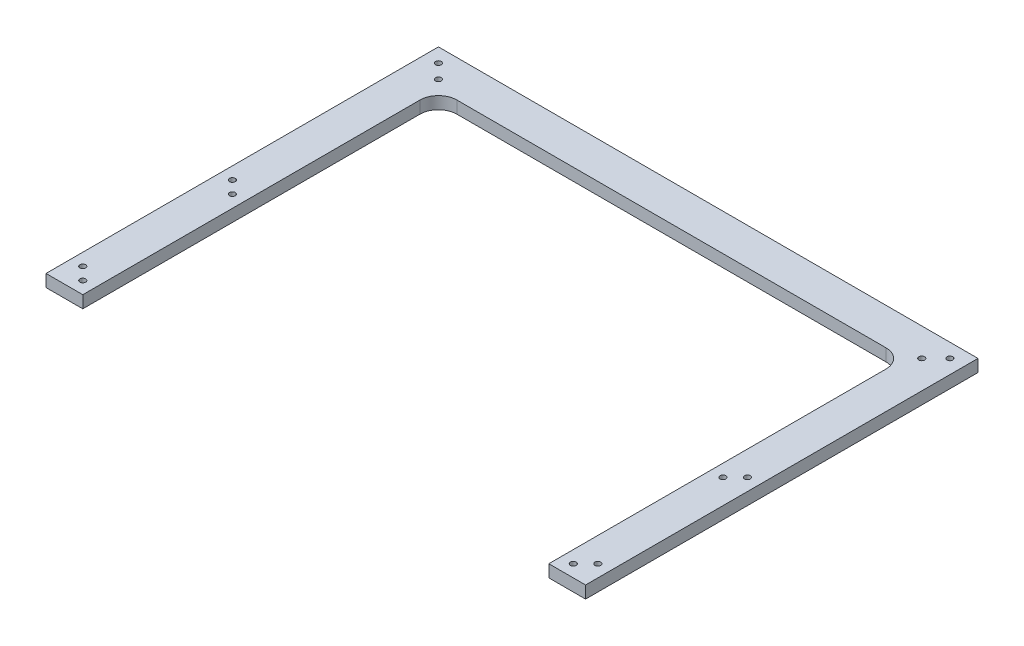
SolidWorks part; units mm, degrees
ref_plane "Front Plane" through (0, 0, 0) normal (0, 0, 1) x (1, 0, 0)
ref_plane "Top Plane" through (0, 0, 0) normal (0, 1, 0) x (1, 0, 0)
ref_plane "Right Plane" through (0, 0, 0) normal (1, 0, 0) x (0, 0, -1)
sketch "Sketch1" plane through (0, 0, 0) normal (0, 1, 0) x (1, 0, 0)
  line L0 (-120.65, -101.6) -> (-120.65, 82.55)
  line L1 (-139.7, -101.6) -> (-120.65, -101.6)
  line L2 (-139.7, -101.6) -> (-139.7, 101.6)
  line L3 (-139.7, 101.6) -> (139.7, 101.6)
  line L4 (139.7, -101.6) -> (139.7, 101.6)
  line L5 (-139.7, -101.6) -> (139.7, 101.6) construction
  line L6 (-139.7, 101.6) -> (139.7, -101.6) construction
  line L7 (-120.65, 82.55) -> (120.65, 82.55)
  line L8 (120.65, -101.6) -> (120.65, 82.55)
  line L9 (120.65, -101.6) -> (139.7, -101.6)
  point P0 (0, 0)
  dimension "D1" = 279.4
  dimension "D2" = 203.2
  dimension "D3" = 19.05
extrude "Boss-Extrude1" add sketch "Sketch1" against normal blind 6.35 contours L0 L7 L8 L9 L4 L3 L2 L1
fillet "Fillet1" radius 9.525 2 edges at (120.65, -3.175, -82.55) (-120.65, -3.175, -82.55)
sketch "Sketch2" plane through (0, 0, 0) normal (0, 1, 0) x (1, 0, 0)
  line L0 (-139.7, -82.55) -> (-120.65, -82.55) construction
  line L2 (0, 0) -> (0, -121.5954) construction
  line L3 (-139.7, -101.6) -> (-139.7, 101.6) construction
  line L4 (-120.65, -101.6) -> (-120.65, 73.025) construction
  line L5 (-120.65, -82.55) -> (-120.65, -101.6) construction
  line L6 (-139.7, -82.55) -> (-133.35, -88.9) construction
  line L7 (-133.35, -88.9) -> (-127, -95.25) construction
  line L8 (-127, -95.25) -> (-120.65, -101.6) construction
  line L9 (139.7, 101.6) -> (132.4201, 94.3201) construction
  line L10 (132.4201, 94.3201) -> (125.1401, 87.0401) construction
  line L11 (125.1401, 87.0401) -> (117.8602, 79.7602) construction
  line L12 (-125.1401, 87.0401) -> (-117.8602, 79.7602) construction
  line L13 (-132.4201, 94.3201) -> (-125.1401, 87.0401) construction
  line L14 (-139.7, 101.6) -> (-132.4201, 94.3201) construction
  circle A2 centre (-133.35, -88.9) radius 1.5
  circle A3 centre (-127, -95.25) radius 1.5
  circle A4 centre (133.35, -88.9) radius 1.5
  circle A5 centre (127, -95.25) radius 1.5
  arc A7 (120.65, 73.025) -> (111.125, 82.55) centre (111.125, 73.025) ccw construction
  circle A8 centre (132.4201, 94.3201) radius 1.5
  circle A9 centre (125.1401, 87.0401) radius 1.5
  circle A10 centre (-125.1401, 87.0401) radius 1.5
  circle A11 centre (-132.4201, 94.3201) radius 1.5
  dimension "D2" = 3
  dimension "D1" = 3
extrude "Cut-Extrude1" cut sketch "Sketch2" against normal through all
pattern_linear "LPattern1" count 2 spacing 77.47 along (0, 0, -1) of "Cut-Extrude1"
